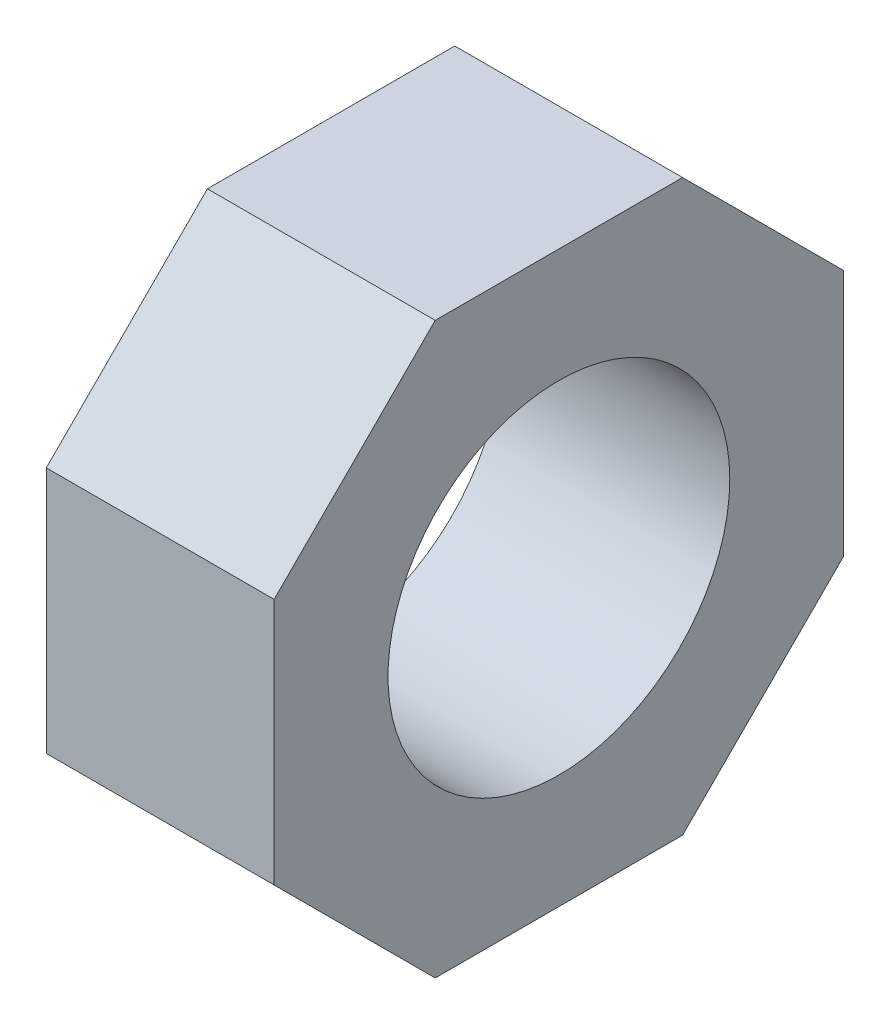
SolidWorks part; units mm, degrees
ref_plane "Front Plane" through (0, 0, 0) normal (0, 0, 1) x (1, 0, 0)
ref_plane "Top Plane" through (0, 0, 0) normal (0, 1, 0) x (1, 0, 0)
ref_plane "Right Plane" through (0, 0, 0) normal (1, 0, 0) x (0, 0, -1)
sketch "Sketch1" plane through (0, 0, 0) normal (1, 0, 0) x (0, 0, -1)
  line L0 (0, 0) -> (0, 2.5) construction
  line L1 (-1.0858, 2.5) -> (1.0858, 2.5)
  line L2 (1.0858, 2.5) -> (2.5, 1.0858)
  line L3 (2.5, 1.0858) -> (2.5, -1.0858)
  line L4 (0, 0) -> (2.5, 0) construction
  line L5 (1.0858, -2.5) -> (2.5, -1.0858)
  line L6 (-1.0858, -2.5) -> (1.0858, -2.5)
  line L7 (-1.0858, -2.5) -> (-2.5, -1.0858)
  line L8 (-2.5, 1.0858) -> (-2.5, -1.0858)
  line L9 (-1.0858, 2.5) -> (-2.5, 1.0858)
  circle A0 centre (0, 0) radius 1.5
  point P7 (3, 1.4464)
  point P12 (0, -2.5)
  point P15 (0, 0)
  dimension "D1" = 3
  dimension "D2" = 2.5
  dimension "D3" = 2.5
  dimension "D4" = 45
  dimension "D5" = 2
extrude "Boss-Extrude1" add sketch "Sketch1" along normal blind 2
